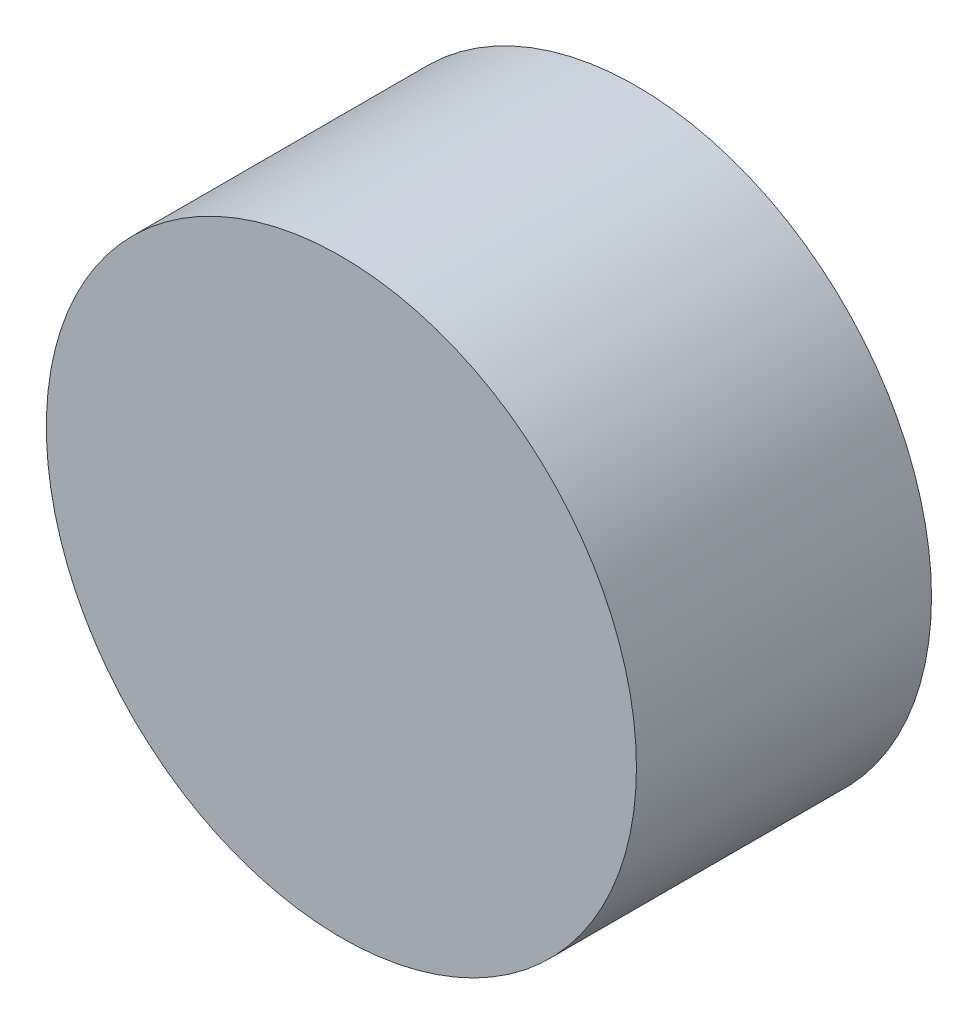
SolidWorks part; units mm, degrees
ref_plane "前视基准面" through (0, 0, 0) normal (0, 0, 1) x (1, 0, 0)
ref_plane "上视基准面" through (0, 0, 0) normal (0, 1, 0) x (1, 0, 0)
ref_plane "右视基准面" through (0, 0, 0) normal (1, 0, 0) x (0, 0, -1)
other "Configuration Table"
sketch "草图1" plane through (0, 0, 0) normal (0, 0, 1) x (1, 0, 0)
  circle A0 centre (0, 0) radius 8
extrude "凸台-拉伸1" add sketch "草图1" along normal blind 8
sketch "草图2" plane through (0, 0, 0) normal (0, 0, 1) x (1, 0, 0)
  circle A0 centre (0, 0) radius 42
sketch "草图3" plane through (0, 0, 0) normal (0, 0, 1) x (1, 0, 0)
  circle A0 centre (0, 0) radius 8
sketch "草图4" plane through (0, 0, 0) normal (0, 0, 1) x (1, 0, 0)
  circle A0 centre (34.1768, 24.412) radius 16.3232
  circle A1 centre (0, 0) radius 42 construction
